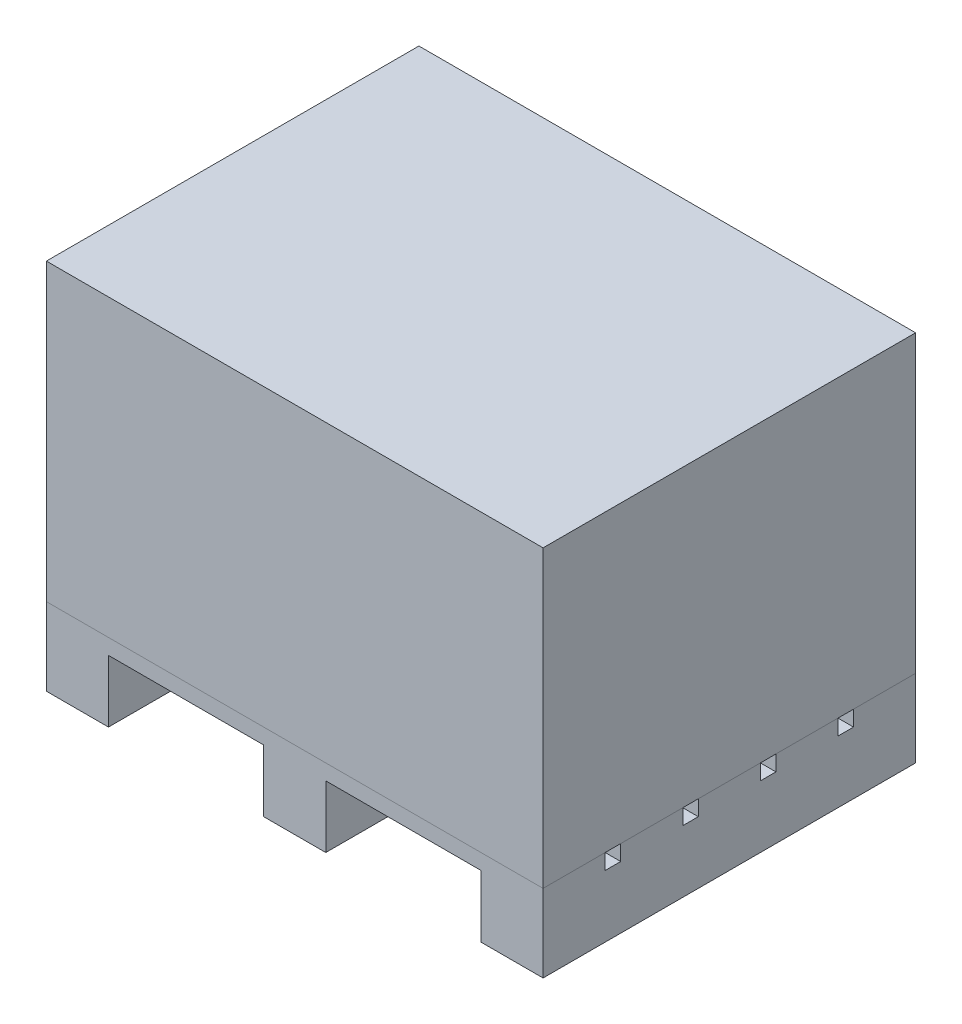
SolidWorks part; units mm, degrees
ref_plane "Alzado" through (0, 0, 0) normal (0, 0, 1) x (1, 0, 0)
ref_plane "Planta" through (0, 0, 0) normal (0, 1, 0) x (1, 0, 0)
ref_plane "Vista lateral" through (0, 0, 0) normal (1, 0, 0) x (0, 0, -1)
sketch "Croquis1" plane through (0, 0, 0) normal (0, 1, 0) x (1, 0, 0)
  line L1 (-56.8494, 21.9312) -> (-46.8494, 21.9312)
  line L2 (-56.8494, 21.9312) -> (-56.8494, -38.0688)
  line L3 (-56.8494, -38.0688) -> (-46.8494, -38.0688)
  line L4 (-46.8494, 21.9312) -> (-46.8494, -38.0688)
  line L5 (-21.8494, 21.9312) -> (-11.8494, 21.9312)
  line L6 (-21.8494, 21.9312) -> (-21.8494, -38.0688)
  line L7 (-21.8494, -38.0688) -> (-11.8494, -38.0688)
  line L8 (-11.8494, 21.9312) -> (-11.8494, -38.0688)
  line L9 (13.1506, 21.9312) -> (23.1506, 21.9312)
  line L10 (13.1506, 21.9312) -> (13.1506, -38.0688)
  line L11 (13.1506, -38.0688) -> (23.1506, -38.0688)
  line L12 (23.1506, 21.9312) -> (23.1506, -38.0688)
  dimension "D1" = 60
  dimension "D2" = 60
  dimension "D3" = 60
  dimension "D4" = 10
  dimension "D5" = 10
  dimension "D6" = 10
  dimension "D7" = 25
  dimension "D8" = 25
extrude "Saliente-Extruir1" add sketch "Croquis1" along normal blind 10
sketch "Croquis2" plane through (0, 10, 0) normal (0, 1, 0) x (1, 0, 0)
  line L0 (23.1506, -38.0688) -> (23.1506, 21.9312) construction
  line L1 (-56.8494, -38.0688) -> (23.1506, -38.0688)
  line L2 (-56.8494, -38.0688) -> (-56.8494, -28.0688)
  line L3 (-56.8494, -28.0688) -> (23.1506, -28.0688)
  line L4 (23.1506, -38.0688) -> (23.1506, -28.0688)
  line L5 (-56.8494, 21.9312) -> (-56.8494, -38.0688) construction
  line L6 (-56.8494, 21.9312) -> (23.1506, 21.9312)
  line L7 (-56.8494, 21.9312) -> (-56.8494, 11.9312)
  line L8 (-56.8494, 11.9312) -> (23.1506, 11.9312)
  line L9 (23.1506, 21.9312) -> (23.1506, 11.9312)
  line L10 (-56.8494, 9.4312) -> (23.1506, 9.4312)
  line L11 (-56.8494, 9.4312) -> (-56.8494, -0.5688)
  line L12 (-56.8494, -0.5688) -> (23.1506, -0.5688)
  line L13 (23.1506, 9.4312) -> (23.1506, -0.5688)
  line L15 (-56.8494, -25.5688) -> (23.1506, -25.5688)
  line L16 (-56.8494, -25.5688) -> (-56.8494, -15.5688)
  line L17 (-56.8494, -15.5688) -> (23.1506, -15.5688)
  line L18 (23.1506, -25.5688) -> (23.1506, -15.5688)
  line L19 (-56.8494, -3.0688) -> (23.1506, -3.0688)
  line L20 (-56.8494, -3.0688) -> (-56.8494, -13.0688)
  line L21 (-56.8494, -13.0688) -> (23.1506, -13.0688)
  line L22 (23.1506, -3.0688) -> (23.1506, -13.0688)
  dimension "D1" = 10
  dimension "D2" = 10
  dimension "D3" = 2.5
  dimension "D4" = 10
  dimension "D5" = 2.5
  dimension "D6" = 10
  dimension "D7" = 10
  dimension "D8" = 2.5
  dimension "D9" = 2.5
extrude "Saliente-Extruir2" add sketch "Croquis2" along normal blind 2.5
sketch "Croquis3" plane through (0, 12.5, 0) normal (0, 1, 0) x (1, 0, 0)
  line L1 (-56.8494, 21.9312) -> (23.1506, 21.9312)
  line L2 (-56.8494, 21.9312) -> (-56.8494, -38.0688)
  line L3 (-56.8494, -38.0688) -> (23.1506, -38.0688)
  line L4 (23.1506, 21.9312) -> (23.1506, -38.0688)
extrude "Saliente-Extruir5" add sketch "Croquis3" along normal blind 47.5 separate body
